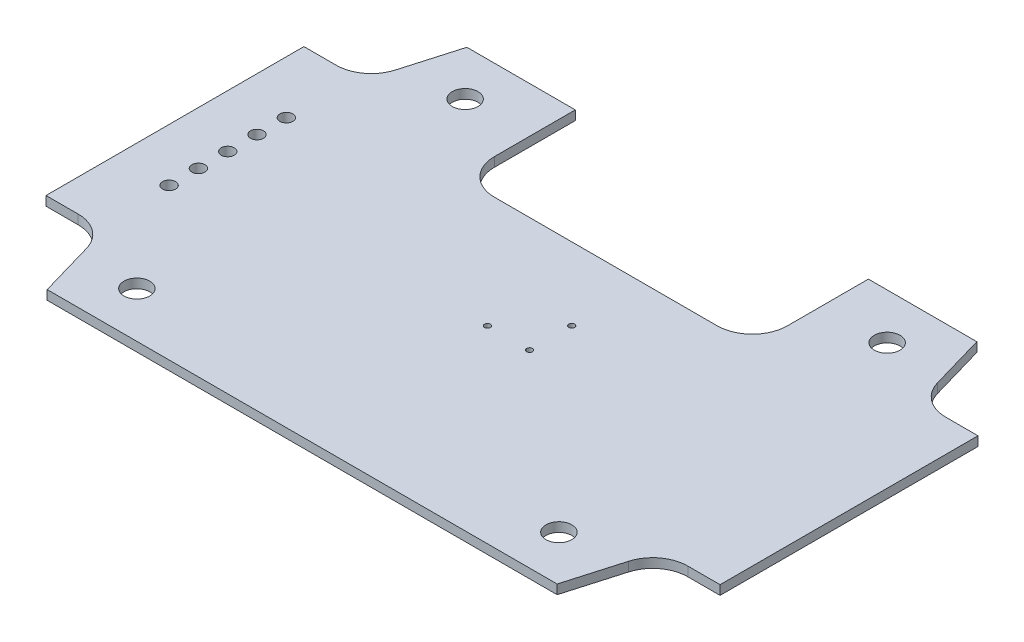
SolidWorks part; units mm, degrees
material "E-Glass Fiber"
ref_plane "Front Plane" through (0, 0, 0) normal (0, 0, 1) x (1, 0, 0)
ref_plane "Top Plane" through (0, 0, 0) normal (0, 1, 0) x (1, 0, 0)
ref_plane "Right Plane" through (0, 0, 0) normal (1, 0, 0) x (0, 0, -1)
sketch "Sketch1" plane through (0, 0, 0) normal (0, 1, 0) x (1, 0, 0)
  line L1 (-0.4366, 0) -> (0.4366, 0) construction
  line L2 (-30.25, -17.9) -> (27.25, -17.9)
  line L3 (-30.25, -17.9) -> (-30.25, 17.9)
  line L4 (-30.25, 17.9) -> (27.25, 17.9)
  line L5 (27.25, -17.9) -> (27.25, 17.9)
  line L6 (-30.25, -17.9) -> (27.25, 17.9) construction
  line L14 (-30.25, 17.9) -> (27.25, -17.9) construction
  line L15 (0, -0.4366) -> (0, 0.4366) construction
  point P0 (0, 0)
  point P1 (-1.5, 0)
  dimension "D1" = 57.5
  dimension "D2" = 35.8
  dimension "D3" = 1.5
extrude "Base Extrusion" add sketch "Sketch1" along normal blind 0.7937
fillet "Corner Rounds" [suppressed] radius 8
sketch "Sketch2" plane through (0, 0.7937, 0) normal (0, 1, 0) x (1, 0, 0)
  line L0 (-1.7961, 1.7961) -> (1.7961, -1.7961) construction
  line L1 (1.7961, 1.7961) -> (0, 0) construction
  line L2 (0, -0.4366) -> (0, 0.4366) construction
  line L3 (-0.4366, 0) -> (0.4366, 0) construction
  circle A0 centre (0, 0) radius 2.54 construction
  circle A1 centre (-1.7961, 1.7961) radius 0.25 construction
  circle A2 centre (1.7961, -1.7961) radius 0.25
  circle A3 centre (1.7961, 1.7961) radius 0.25
  circle A4 centre (-1.7961, -1.7961) radius 0.25
  dimension "D1" = 0.5
  dimension "D2" = 5.08
  dimension "D3" = 0
extrude "PIR Mounting Holes" cut sketch "Sketch2" against normal through all
other "Axial Bend" [suppressed] parameters "D0"=35, "D1"=0.5, "D2"=0.5
sketch "Sketch3" plane through (0, 0.7937, 0) normal (0, 1, 0) x (1, 0, 0)
  line L0 (-0.4366, 0) -> (0.4366, 0) construction
  line L1 (0, -0.4366) -> (0, 0.4366) construction
  circle A0 centre (-25.75, 5) radius 0.555
  dimension "D1" = 1.11
  dimension "D2" = 5
  dimension "D3" = 25.75
extrude "Connector Mounting Hole" cut sketch "Sketch3" against normal through all
pattern_linear "Connector Mounting Hole Pattern" count 5 spacing 2.5 along (0, 0, 1) of "Connector Mounting Hole"
sketch "Sketch4" plane through (0, 0, 0) normal (0, -1, 0) x (1, 0, 0)
  line L1 (11, -8) -> (-14, -8)
  line L2 (11, -8) -> (11, -17.9)
  line L3 (11, -17.9) -> (-14, -17.9)
  line L4 (-14, -8) -> (-14, -17.9)
  line L5 (11, -8) -> (-14, -17.9) construction
  line L6 (11, -17.9) -> (-14, -8) construction
  line L7 (27.25, -17.9) -> (-30.25, -17.9) construction
  line L8 (0.4366, 0) -> (-0.4366, 0) construction
  line L9 (27.25, -17.9) -> (-30.25, -17.9) construction
  line L10 (0, -0.4366) -> (0, 0.4366) construction
  point P12 (-1.5, -12.95)
  dimension "D1" = 25
  dimension "D2" = 8
  dimension "D3" = 1.5
extrude "LED Driver Clearance Cut" cut sketch "Sketch4" against normal through all
fillet "LED Driver Clearance Cut Fillets" radius 3 2 edges at (-14, 0.3969, -8) (11, 0.3969, -8)
sketch "Sketch5" plane through (0, 0.7937, 0) normal (0, 1, 0) x (1, 0, 0)
  line L0 (-30.25, 11) -> (-27.5, 11)
  line L1 (-24.618, 13.167) -> (-23.25, 17.9)
  line L2 (-23.25, 17.9) -> (-30.25, 17.9)
  line L3 (-30.25, 17.9) -> (-30.25, 11)
  line L4 (-30.25, 17.9) -> (-30.25, -17.9) construction
  line L5 (-14, 17.9) -> (-30.25, 17.9) construction
  line L6 (20.25, 17.9) -> (21.618, 13.167)
  line L7 (27.25, 17.9) -> (11, 17.9) construction
  line L8 (24.5, 11) -> (27.25, 11)
  line L9 (27.25, -17.9) -> (27.25, 17.9) construction
  line L10 (27.25, 11) -> (27.25, 17.9)
  line L11 (20.25, 17.9) -> (27.25, 17.9)
  arc A1 (-27.5, 11) -> (-24.618, 13.167) centre (-27.5, 14) ccw
  arc A2 (21.618, 13.167) -> (24.5, 11) centre (24.5, 14) ccw
  dimension "D1" = 27.5
  dimension "D3" = 3
  dimension "D4" = 52
  dimension "D2" = 14
  dimension "D5" = 7
extrude "Corner Cutout" cut sketch "Sketch5" against normal through all
mirror "Corner Cut Mirror" about plane through (0, 0, 0) normal (0, 0, 1) of "Corner Cutout"
sketch "Sketch7" plane through (0, 0.7937, 0) normal (0, 1, 0) x (1, 0, 0)
  line L0 (-0.4366, 0) -> (0.4366, 0) construction
  line L1 (16.5, -14) -> (-19.5, -14) construction
  line L2 (16.5, -14) -> (16.5, 14) construction
  line L3 (16.5, 14) -> (-19.5, 14) construction
  line L4 (-19.5, -14) -> (-19.5, 14) construction
  line L5 (16.5, -14) -> (-19.5, 14) construction
  line L6 (16.5, 14) -> (-19.5, -14) construction
  line L7 (0, -0.4366) -> (0, 0.4366) construction
  circle A0 centre (-19.5, 14) radius 1.1
  circle A1 centre (-19.5, -14) radius 1.1
  circle A2 centre (16.5, -14) radius 1.1
  circle A3 centre (16.5, 14) radius 1.1
  point P0 (-1.5, 0)
  dimension "D4" = 2.2
  dimension "D1" = 1.5
  dimension "D2" = 36
  dimension "D3" = 28
extrude "Mounting Screw Holes" cut sketch "Sketch7" against normal through all
sketch "Sketch8" plane through (0, 0.7937, 0) normal (0, 1, 0) x (1, 0, 0)
  line L0 (-14, 17.9) -> (-23.25, 17.9) construction
  line L1 (-20.6, 14) -> (-18.4, 14)
  line L2 (-20.6, 14) -> (-20.6, 17.9)
  line L3 (-20.6, 17.9) -> (-18.4, 17.9)
  line L4 (-18.4, 14) -> (-18.4, 17.9)
  line L5 (20.25, 17.9) -> (11, 17.9) construction
  line L6 (15.4, 14) -> (17.6, 14)
  line L7 (15.4, 14) -> (15.4, 17.9)
  line L8 (15.4, 17.9) -> (17.6, 17.9)
  line L9 (17.6, 14) -> (17.6, 17.9)
  line L10 (-23.25, -17.9) -> (20.25, -17.9) construction
  line L11 (15.4, -14) -> (17.6, -14)
  line L12 (15.4, -14) -> (15.4, -17.9)
  line L13 (15.4, -17.9) -> (17.6, -17.9)
  line L14 (17.6, -14) -> (17.6, -17.9)
  line L16 (-20.6, -14) -> (-18.4, -14)
  line L17 (-20.6, -14) -> (-20.6, -17.9)
  line L18 (-20.6, -17.9) -> (-18.4, -17.9)
  line L19 (-18.4, -14) -> (-18.4, -17.9)
  circle A0 centre (-19.5, 14) radius 1.1 construction
  circle A1 centre (16.5, 14) radius 1.1 construction
  circle A2 centre (16.5, -14) radius 1.1 construction
  circle A3 centre (-19.5, -14) radius 1.1 construction
extrude "Mounting Screw Slots" [suppressed] cut sketch "Sketch8" against normal through all
